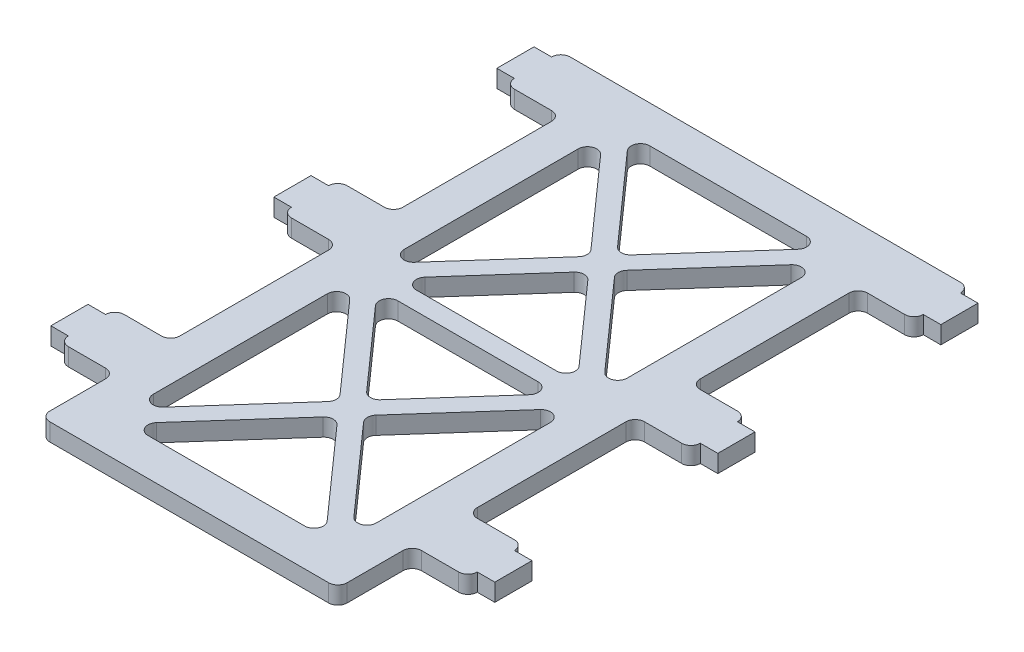
SolidWorks part; units mm, degrees
ref_plane "Front Plane" through (0, 0, 0) normal (0, 0, 1) x (1, 0, 0)
ref_plane "Top Plane" through (0, 0, 0) normal (0, 1, 0) x (1, 0, 0)
ref_plane "Right Plane" through (0, 0, 0) normal (1, 0, 0) x (0, 0, -1)
sketch "Sketch1" plane through (0, 34.29, 0) normal (0, 1, 0) x (1, 0, 0)
  line L0 (28.7528, 184.15) -> (31.75, 184.15) construction
  line L1 (0, -190.5) -> (0, 187.198) construction
  line L2 (38.1028, 187.198) -> (35.1028, 187.198) construction
  line L3 (35.1028, -190.5) -> (38.1, -190.5) construction
  line L5 (-25.4, 71.4375) -> (25.4, 71.4375)
  line L6 (-25.4, 71.4375) -> (-25.4, 169.8625)
  line L7 (-25.4, 169.8625) -> (25.4, 169.8625)
  line L8 (25.4, 71.4375) -> (25.4, 169.8625)
  line L9 (-25.4, 71.4375) -> (25.4, 169.8625) construction
  line L10 (-25.4, 169.8625) -> (25.4, 71.4375) construction
  point P0 (0, 120.65)
  dimension "D1" = 98.425
  dimension "D2" = 50.8
  dimension "D3" = 14.2875
extrude "Boss-Extrude1" add sketch "Sketch1" along normal mid plane 3 contours L7 L8 L5 L6
sketch "Sketch2" plane through (0, 35.79, 0) normal (0, 1, 0) x (1, 0, 0)
  line L0 (0, 169.8625) -> (0, 65.0186) construction
  line L1 (-25.4, 169.8625) -> (25.4, 169.8625) construction
  line L2 (25.4, 127) -> (-25.4, 127) construction
  line L5 (-34.925, 169.8625) -> (-25.4, 160.3375) construction
  line L6 (34.925, 160.3375) -> (25.4, 160.3375)
  line L7 (34.925, 160.3375) -> (34.925, 169.8625)
  line L8 (34.925, 169.8625) -> (25.4, 169.8625)
  line L9 (25.4, 160.3375) -> (25.4, 169.8625)
  line L10 (34.925, 160.3375) -> (25.4, 169.8625) construction
  line L11 (34.925, 169.8625) -> (25.4, 160.3375) construction
  line L12 (-34.925, 160.3375) -> (-25.4, 169.8625) construction
  line L13 (-25.4, 160.3375) -> (-25.4, 169.8625)
  line L14 (-34.925, 169.8625) -> (-25.4, 169.8625)
  line L15 (-34.925, 160.3375) -> (-34.925, 169.8625)
  line L16 (-34.925, 160.3375) -> (-25.4, 160.3375)
  line L17 (34.925, 122.2375) -> (25.4, 122.2375)
  line L18 (34.925, 122.2375) -> (34.925, 131.7625)
  line L19 (34.925, 131.7625) -> (25.4, 131.7625)
  line L20 (25.4, 122.2375) -> (25.4, 131.7625)
  line L21 (34.925, 122.2375) -> (25.4, 131.7625) construction
  line L22 (34.925, 131.7625) -> (25.4, 122.2375) construction
  line L23 (-25.4, 122.2375) -> (-25.4, 131.7625)
  line L24 (-34.925, 131.7625) -> (-25.4, 131.7625)
  line L25 (-34.925, 122.2375) -> (-34.925, 131.7625)
  line L26 (-34.925, 122.2375) -> (-25.4, 122.2375)
  line L27 (-34.925, 131.7625) -> (-25.4, 122.2375) construction
  line L28 (-34.925, 122.2375) -> (-25.4, 131.7625) construction
  line L29 (34.925, 84.1375) -> (25.4, 84.1375)
  line L30 (34.925, 84.1375) -> (34.925, 93.6625)
  line L31 (34.925, 93.6625) -> (25.4, 93.6625)
  line L32 (25.4, 84.1375) -> (25.4, 93.6625)
  line L33 (34.925, 84.1375) -> (25.4, 93.6625) construction
  line L34 (34.925, 93.6625) -> (25.4, 84.1375) construction
  line L35 (-25.4, 84.1375) -> (-25.4, 93.6625)
  line L36 (-34.925, 93.6625) -> (-25.4, 93.6625)
  line L37 (-34.925, 84.1375) -> (-34.925, 93.6625)
  line L38 (-34.925, 84.1375) -> (-25.4, 84.1375)
  line L39 (-34.925, 93.6625) -> (-25.4, 84.1375) construction
  line L40 (-34.925, 84.1375) -> (-25.4, 93.6625) construction
  point P9 (0, 0)
  point P11 (30.1625, 165.1)
  point P21 (-30.1625, 165.1)
  point P22 (0, 0)
  point P24 (30.1625, 127)
  point P33 (-30.1625, 127)
  point P34 (30.1625, 88.9)
  point P43 (-30.1625, 88.9)
  dimension "D1" = 9.525
  dimension "D2" = 9.525
  dimension "D4" = 38.1
  dimension "D3" = 3
extrude "Boss-Extrude2" add sketch "Sketch2" against normal up to surface (3 mm away) up to face at (0, 32.79, -120.65)
sketch "Sketch4" plane through (0, 35.79, 0) normal (0, 1, 0) x (1, 0, 0)
  line L0 (25.4, 131.7625) -> (25.4, 160.3375) construction
  line L1 (-19.05, 163.5125) -> (19.05, 163.5125)
  line L2 (-19.05, 163.5125) -> (-19.05, 77.7875)
  line L3 (-19.05, 77.7875) -> (19.05, 77.7875)
  line L4 (19.05, 163.5125) -> (19.05, 77.7875)
  line L5 (-19.05, 163.5125) -> (19.05, 77.7875) construction
  line L6 (-19.05, 77.7875) -> (19.05, 163.5125) construction
  line L7 (-25.4, 131.7625) -> (-25.4, 160.3375) construction
  line L8 (-34.925, 169.8625) -> (34.925, 169.8625) construction
  line L9 (-25.4, 71.4375) -> (25.4, 71.4375) construction
  line L10 (-19.05, 120.65) -> (19.05, 120.65) construction
  line L11 (19.05, 120.65) -> (-19.05, 163.5125) construction
  line L12 (19.05, 120.65) -> (-19.05, 77.7875) construction
  line L13 (-19.05, 120.65) -> (19.05, 163.5125) construction
  line L14 (19.05, 77.7875) -> (-19.05, 120.65) construction
  line L15 (-19.05, 119.0625) -> (19.05, 119.0625)
  line L16 (-19.05, 122.2375) -> (19.05, 122.2375)
  line L17 (20.2365, 78.8422) -> (-16.926, 120.65)
  line L18 (-16.926, 120.65) -> (20.2365, 162.4578)
  line L19 (21.174, 120.65) -> (-17.8635, 76.7328)
  line L20 (21.174, 120.65) -> (-17.8635, 164.5672)
  line L21 (17.8635, 76.7328) -> (-21.174, 120.65)
  line L22 (-21.174, 120.65) -> (17.8635, 164.5672)
  line L23 (16.926, 120.65) -> (-20.2365, 78.8422)
  line L24 (16.926, 120.65) -> (-20.2365, 162.4578)
  point P0 (0, 120.65)
  dimension "D1" = 6.35
  dimension "D2" = 6.35
  dimension "D3" = 6.35
  dimension "D4" = 6.35
  dimension "D5" = 1.5875
  dimension "D6" = 1.5875
  dimension "D7" = 1.5875
  dimension "D8" = 1.5875
extrude "Cut-Extrude1" cut sketch "Sketch4" against normal blind 3 contours L15 L19 L17 L4 | L3 L21 L19 | L23 L21 L15 L2 | L23 L15 L17 | L16 L24 L18 | L20 L16 L4 L18 | L20 L22 L1 | L22 L24 L2 L16
fillet "Fillet1" radius 1.5875 48 edges at (-15.5149, 34.29, -119.0625) (15.5149, 34.29, -119.0625) (0, 34.29, -101.6083) (-19.05, 34.29, -118.2605) (-2.124, 34.29, -99.2187) (-19.05, 34.29, -80.177) (19.05, 34.29, -161.123) (19.05, 34.29, -123.0395) (2.124, 34.29, -142.0813) (16.926, 34.29, -163.5125) (0, 34.29, -144.4708) (-16.926, 34.29, -163.5125) (2.124, 34.29, -99.2187) (19.05, 34.29, -118.2605) (19.05, 34.29, -80.177) (34.925, 34.29, -84.1375) (34.925, 34.29, -93.6625) (25.4, 34.29, -93.6625) (25.4, 34.29, -122.2375) (34.925, 34.29, -122.2375) (34.925, 34.29, -131.7625) (25.4, 34.29, -131.7625) (25.4, 34.29, -160.3375) (34.925, 34.29, -160.3375) (34.925, 34.29, -169.8625) (-34.925, 34.29, -160.3375) (-25.4, 34.29, -160.3375) (-25.4, 34.29, -131.7625) (-34.925, 34.29, -131.7625) (-34.925, 34.29, -122.2375) (-25.4, 34.29, -122.2375) (-25.4, 34.29, -93.6625) (-34.925, 34.29, -93.6625) (-19.05, 34.29, -123.0395) (-19.05, 34.29, -161.123) (-2.124, 34.29, -142.0813) (-16.926, 34.29, -77.7875) (0, 34.29, -96.8292) (16.926, 34.29, -77.7875) (-15.5149, 34.29, -122.2375) (0, 34.29, -139.6917) (15.5149, 34.29, -122.2375) (-34.925, 34.29, -169.8625) (-25.4, 34.29, -71.4375) (25.4, 34.29, -71.4375) (25.4, 34.29, -84.1375) (-34.925, 34.29, -84.1375) (-25.4, 34.29, -84.1375)
sketch "Sketch5" plane through (0, 35.79, 0) normal (0, 1, 0) x (1, 0, 0)
  line L0 (34.925, 161.925) -> (34.925, 168.275) construction
  line L1 (37.925, 161.925) -> (34.925, 161.925)
  line L2 (37.925, 161.925) -> (37.925, 168.275)
  line L3 (37.925, 168.275) -> (34.925, 168.275)
  line L4 (34.925, 161.925) -> (34.925, 168.275)
  line L5 (37.925, 161.925) -> (34.925, 168.275) construction
  line L6 (37.925, 168.275) -> (34.925, 161.925) construction
  line L7 (34.925, 161.925) -> (34.925, 168.275) construction
  line L8 (34.925, 165.1) -> (36.425, 165.1) construction
  line L9 (0, 196.0278) -> (0, 0) construction
  line L10 (-34.925, 165.1) -> (-36.425, 165.1) construction
  line L11 (-37.925, 168.275) -> (-34.925, 161.925) construction
  line L12 (-37.925, 161.925) -> (-34.925, 168.275) construction
  line L13 (-34.925, 161.925) -> (-34.925, 168.275)
  line L14 (-37.925, 168.275) -> (-34.925, 168.275)
  line L15 (-37.925, 161.925) -> (-37.925, 168.275)
  line L16 (-37.925, 161.925) -> (-34.925, 161.925)
  line L17 (37.925, 123.825) -> (34.925, 123.825)
  line L18 (37.925, 123.825) -> (37.925, 130.175)
  line L19 (37.925, 130.175) -> (34.925, 130.175)
  line L20 (34.925, 123.825) -> (34.925, 130.175)
  line L21 (37.925, 123.825) -> (34.925, 130.175) construction
  line L22 (37.925, 130.175) -> (34.925, 123.825) construction
  line L23 (34.925, 127) -> (36.425, 127) construction
  line L24 (-34.925, 123.825) -> (-34.925, 130.175)
  line L25 (-37.925, 130.175) -> (-34.925, 130.175)
  line L26 (-37.925, 123.825) -> (-37.925, 130.175)
  line L27 (-37.925, 123.825) -> (-34.925, 123.825)
  line L28 (-34.925, 127) -> (-36.425, 127) construction
  line L29 (-37.925, 130.175) -> (-34.925, 123.825) construction
  line L30 (-37.925, 123.825) -> (-34.925, 130.175) construction
  line L31 (37.925, 85.725) -> (34.925, 85.725)
  line L32 (37.925, 85.725) -> (37.925, 92.075)
  line L33 (37.925, 92.075) -> (34.925, 92.075)
  line L34 (34.925, 85.725) -> (34.925, 92.075)
  line L35 (37.925, 85.725) -> (34.925, 92.075) construction
  line L36 (37.925, 92.075) -> (34.925, 85.725) construction
  line L37 (34.925, 88.9) -> (36.425, 88.9) construction
  line L38 (-34.925, 85.725) -> (-34.925, 92.075)
  line L39 (-37.925, 92.075) -> (-34.925, 92.075)
  line L40 (-37.925, 85.725) -> (-37.925, 92.075)
  line L41 (-37.925, 85.725) -> (-34.925, 85.725)
  line L42 (-34.925, 88.9) -> (-36.425, 88.9) construction
  line L43 (-37.925, 92.075) -> (-34.925, 85.725) construction
  line L44 (-37.925, 85.725) -> (-34.925, 92.075) construction
  line L45 (-36.425, 165.1) -> (-36.425, 127) construction
  point P0 (36.425, 165.1)
  point P7 (36.425, 127)
  point P21 (-36.425, 165.1)
  point P35 (-36.425, 127)
  point P36 (36.425, 88.9)
  point P49 (-36.425, 88.9)
  dimension "D1" = 3
  dimension "D2" = 6.35
  dimension "D4" = 38.1
  dimension "D3" = 3
extrude "Boss-Extrude3" add sketch "Sketch5" against normal up to surface (3 mm away)
